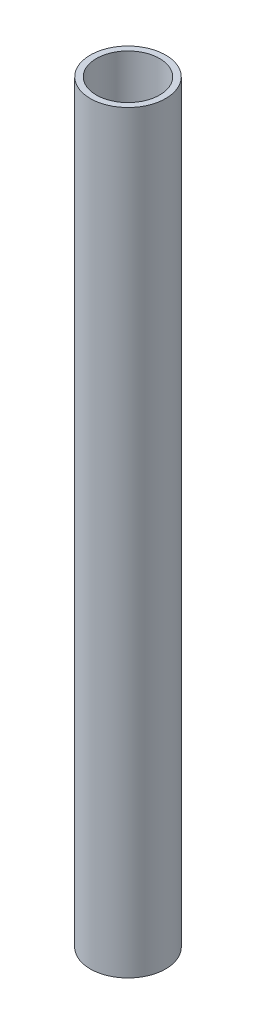
SolidWorks part; units mm, degrees
ref_plane "Alzado" through (0, 0, 0) normal (0, 0, 1) x (1, 0, 0)
ref_plane "Planta" through (0, 0, 0) normal (0, 1, 0) x (1, 0, 0)
ref_plane "Vista lateral" through (0, 0, 0) normal (1, 0, 0) x (0, 0, -1)
sketch "Croquis1" plane through (0, 0, 0) normal (0, 1, 0) x (1, 0, 0)
  circle A0 centre (0, 0) radius 12.5
  circle A1 centre (0, 0) radius 10.5
  dimension "D1" = 25
  dimension "D2" = 2
extrude "Saliente-Extruir1" add sketch "Croquis1" along normal blind 250
